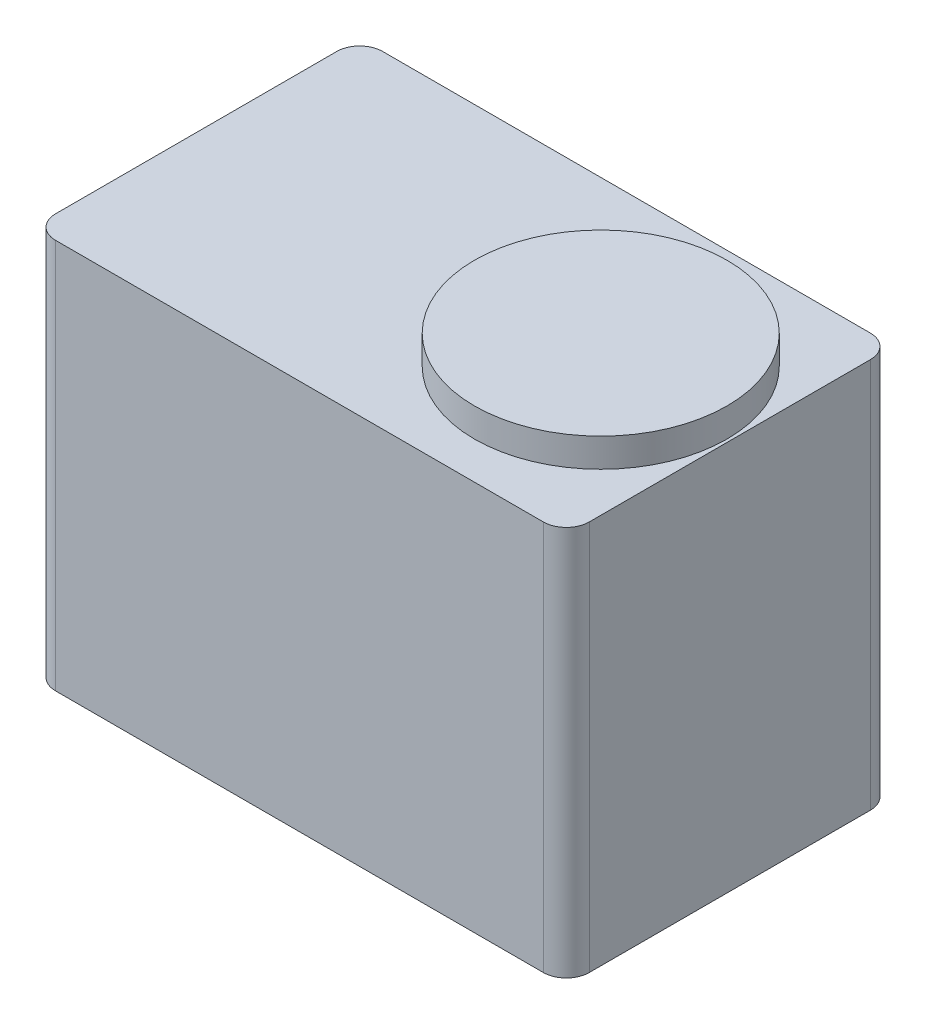
SolidWorks part; units mm, degrees
material "PA Type 6"
ref_plane "Front Plane" through (0, 0, 0) normal (0, 0, 1) x (1, 0, 0)
ref_plane "Top Plane" through (0, 0, 0) normal (0, 1, 0) x (1, 0, 0)
ref_plane "Right Plane" through (0, 0, 0) normal (1, 0, 0) x (0, 0, -1)
sketch "SK_1" plane through (0, 0, 0) normal (0, 1, 0) x (1, 0, 0)
  line L1 (-21.25, -14.25) -> (21.25, -14.25)
  line L2 (-23.25, -12.25) -> (-23.25, 12.25)
  line L3 (-21.25, 14.25) -> (21.25, 14.25)
  line L4 (23.25, -12.25) -> (23.25, 12.25)
  line L5 (-23.25, -14.25) -> (23.25, 14.25) construction
  line L6 (-23.25, 14.25) -> (23.25, -14.25) construction
  arc A0 (21.25, -14.25) -> (23.25, -12.25) centre (21.25, -12.25) ccw
  arc A1 (-23.25, 12.25) -> (-21.25, 14.25) centre (-21.25, 12.25) cw
  arc A2 (-21.25, -14.25) -> (-23.25, -12.25) centre (-21.25, -12.25) cw
  arc A3 (21.25, 14.25) -> (23.25, 12.25) centre (21.25, 12.25) cw
  point P0 (0, 0)
  dimension "D1" = 2
  dimension "W1" = 46.5
  dimension "H1" = 28.5
  dimension "X1" = 23.25
  dimension "Y1" = 14.25
extrude "Housing" add sketch "SK_1" along normal blind 34 from offset 17
sketch "SK_2" plane through (0, 0, 0) normal (0, 1, 0) x (1, 0, 0)
  circle A0 centre (12, 0) radius 11
  dimension "Dia1" = 22
  dimension "X1" = 12
extrude "Horn" add sketch "SK_2" along normal blind 2.5 from offset 17
sketch "SK_3" plane through (0, 0, 0) normal (0, 1, 0) x (1, 0, 0)
  circle A0 centre (12, 0) radius 7
  dimension "X1" = 12
  dimension "Dia1" = 14
extrude "Idler" add sketch "SK_3" along normal blind 1.5 from offset 18.5
equation "\"XM_L\" = 46.5 'DYNAMIXEL XM430 length"
equation "\"XM_W\" = 28.5 'DYNAMIXEL XM430 width"
equation "\"XM_D\" = 34 'DYNAMIXEL XM430 depth (along horn axis)"
equation "\"Horn_Off\" = 12 'horn axis offset from body centre"
equation "\"Horn_D\" = 22 'horn diameter"
equation "\"Horn_T\" = 2.5 'horn thickness"
equation "\"W1@SK_1\" = \"XM_L\""
equation "\"H1@SK_1\" = \"XM_W\""
equation "\"X1@SK_1\" = -((0)-(\"XM_L\")/2)"
equation "\"Y1@SK_1\" = -((0)-(\"XM_W\")/2)"
equation "\"D1@Housing\" = (\"XM_D\"/2)-(-\"XM_D\"/2)"
equation "\"D19@Housing\" = -(-\"XM_D\"/2)"
equation "\"Dia1@SK_2\" = \"Horn_D\""
equation "\"X1@SK_2\" = \"Horn_Off\""
equation "\"D1@Horn\" = (\"XM_D\"/2 + \"Horn_T\")-(\"XM_D\"/2)"
equation "\"D19@Horn\" = \"XM_D\"/2"
equation "\"X1@SK_3\" = \"Horn_Off\""
equation "\"D1@Idler\" = (-\"XM_D\"/2)-(-\"XM_D\"/2 - 1.5)"
equation "\"D19@Idler\" = -(-\"XM_D\"/2 - 1.5)"
